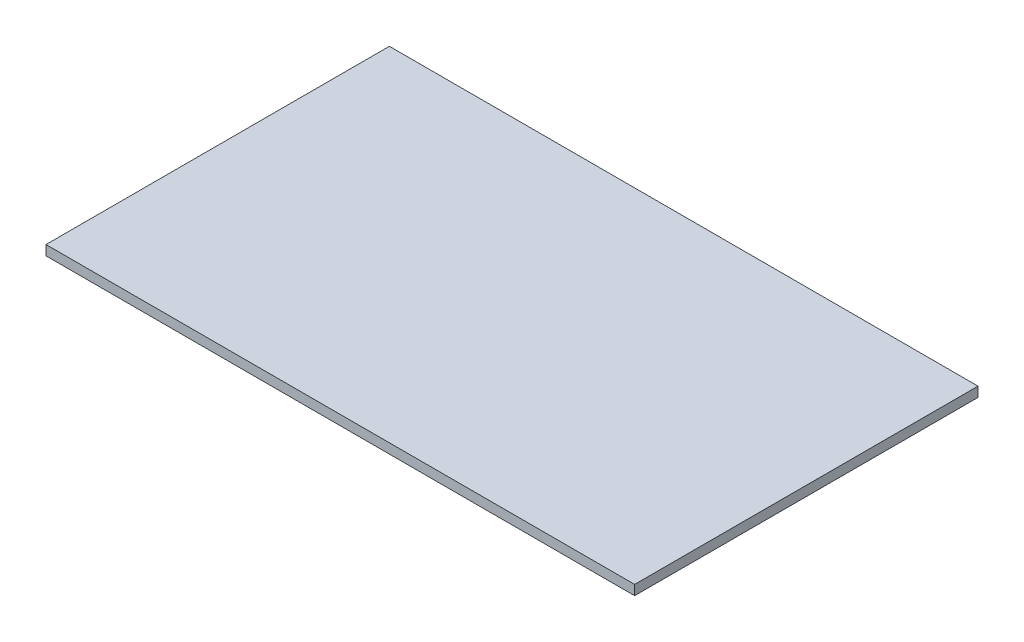
SolidWorks part; units mm, degrees
ref_plane "Front Plane" through (0, 0, 0) normal (0, 0, 1) x (1, 0, 0)
ref_plane "Top Plane" through (0, 0, 0) normal (0, 1, 0) x (1, 0, 0)
ref_plane "Right Plane" through (0, 0, 0) normal (1, 0, 0) x (0, 0, -1)
sketch "Sketch1" plane through (0, 0, 0) normal (0, 1, 0) x (1, 0, 0)
  line L1 (-300, 175) -> (300, 175)
  line L2 (-300, 175) -> (-300, -175)
  line L3 (-300, -175) -> (300, -175)
  line L4 (300, 175) -> (300, -175)
  line L5 (-300, 175) -> (300, -175) construction
  line L6 (-300, -175) -> (300, 175) construction
  point P0 (0, 0)
  dimension "D1" = 350
  dimension "D2" = 600
extrude "Boss-Extrude1" add sketch "Sketch1" along normal blind 10
